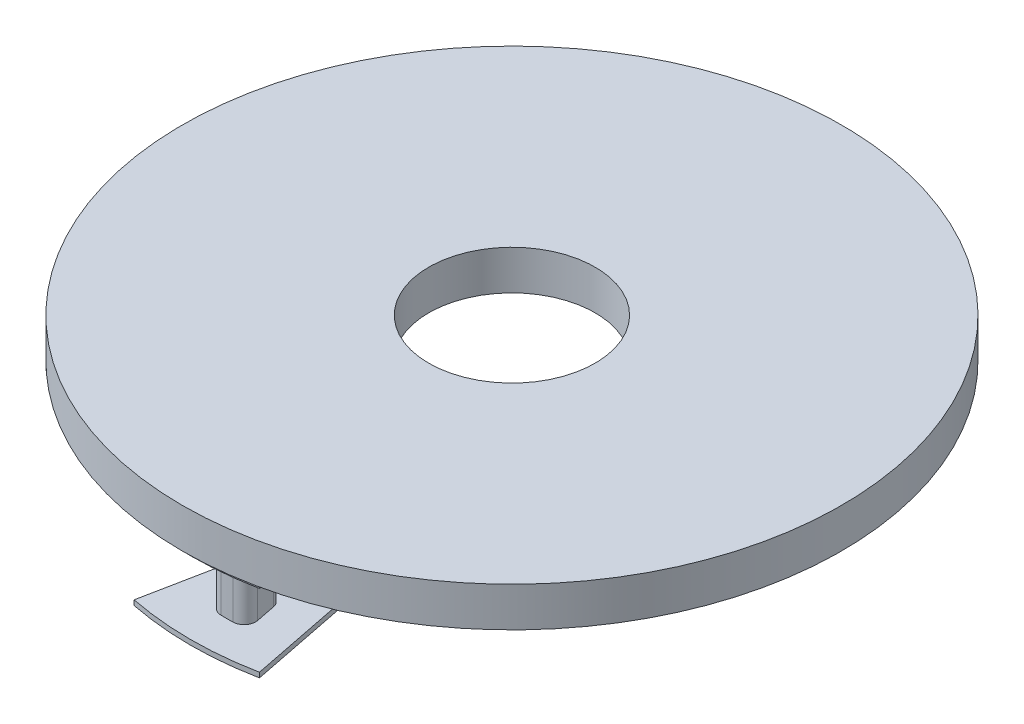
SolidWorks part; units mm, degrees
ref_plane "Front Plane" through (0, 0, 0) normal (0, 0, 1) x (1, 0, 0)
ref_plane "Top Plane" through (0, 0, 0) normal (0, 1, 0) x (1, 0, 0)
ref_plane "Right Plane" through (0, 0, 0) normal (1, 0, 0) x (0, 0, -1)
sketch "Sketch1" plane through (0, 0, 0) normal (0, 1, 0) x (1, 0, 0)
  circle A0 centre (0, 0) radius 100
  circle A1 centre (0, 0) radius 5 construction
  dimension "D1" = 200
  dimension "D2" = 10
extrude "Boss-Extrude1" add sketch "Sketch1" along normal mid plane 12
sketch "Sketch2" plane through (0, -6, 0) normal (0, -1, 0) x (1, 0, 0)
  line L0 (0, 81) -> (0, -37.3915) construction
  line L1 (11.7756, 85.47) -> (9.776, 75.4169)
  line L2 (-5.125, 86.125) -> (5.125, 86.125)
  line L3 (-5.125, 86.125) -> (-5.125, 75.875)
  line L4 (-5.125, 75.875) -> (5.125, 75.875)
  line L5 (5.125, 86.125) -> (5.125, 75.875)
  line L6 (-5.125, 86.125) -> (5.125, 75.875) construction
  line L7 (-5.125, 75.875) -> (5.125, 86.125) construction
  line L8 (11.7756, 85.47) -> (21.8287, 83.4703)
  line L9 (21.8287, 83.4703) -> (19.829, 73.4172)
  line L10 (9.776, 75.4169) -> (19.829, 73.4172)
  line L11 (28.2237, 81.5304) -> (24.3012, 72.0606)
  line L12 (28.2237, 81.5304) -> (37.6935, 77.6079)
  line L13 (37.6935, 77.6079) -> (33.771, 68.1381)
  line L14 (24.3012, 72.0606) -> (33.771, 68.1381)
  line L15 (43.5872, 74.4576) -> (37.8926, 65.9351)
  line L16 (43.5872, 74.4576) -> (52.1098, 68.763)
  line L17 (52.1098, 68.763) -> (46.4152, 60.2405)
  line L18 (37.8926, 65.9351) -> (46.4152, 60.2405)
  line L19 (57.2756, 64.5235) -> (50.0278, 57.2756)
  line L20 (57.2756, 64.5235) -> (64.5235, 57.2756)
  line L21 (64.5235, 57.2756) -> (57.2756, 50.0278)
  line L22 (50.0278, 57.2756) -> (57.2756, 50.0278)
  line L23 (68.763, 52.1098) -> (60.2405, 46.4152)
  line L24 (68.763, 52.1098) -> (74.4576, 43.5872)
  line L25 (74.4576, 43.5872) -> (65.9351, 37.8926)
  line L26 (60.2405, 46.4152) -> (65.9351, 37.8926)
  line L27 (77.6079, 37.6935) -> (68.1381, 33.771)
  line L28 (77.6079, 37.6935) -> (81.5304, 28.2237)
  line L29 (81.5304, 28.2237) -> (72.0606, 24.3012)
  line L30 (68.1381, 33.771) -> (72.0606, 24.3012)
  line L31 (83.4703, 21.8287) -> (73.4172, 19.829)
  line L32 (83.4703, 21.8287) -> (85.47, 11.7756)
  line L33 (85.47, 11.7756) -> (75.4169, 9.776)
  line L34 (73.4172, 19.829) -> (75.4169, 9.776)
  line L35 (86.125, 5.125) -> (75.875, 5.125)
  line L36 (86.125, 5.125) -> (86.125, -5.125)
  line L37 (86.125, -5.125) -> (75.875, -5.125)
  line L38 (75.875, 5.125) -> (75.875, -5.125)
  line L39 (85.47, -11.7756) -> (75.4169, -9.776)
  line L40 (85.47, -11.7756) -> (83.4703, -21.8287)
  line L41 (83.4703, -21.8287) -> (73.4172, -19.829)
  line L42 (75.4169, -9.776) -> (73.4172, -19.829)
  line L43 (81.5304, -28.2237) -> (72.0606, -24.3012)
  line L44 (81.5304, -28.2237) -> (77.6079, -37.6935)
  line L45 (77.6079, -37.6935) -> (68.1381, -33.771)
  line L46 (72.0606, -24.3012) -> (68.1381, -33.771)
  line L47 (74.4576, -43.5872) -> (65.9351, -37.8926)
  line L48 (74.4576, -43.5872) -> (68.763, -52.1098)
  line L49 (68.763, -52.1098) -> (60.2405, -46.4152)
  line L50 (65.9351, -37.8926) -> (60.2405, -46.4152)
  line L51 (64.5235, -57.2756) -> (57.2756, -50.0278)
  line L52 (64.5235, -57.2756) -> (57.2756, -64.5235)
  line L53 (57.2756, -64.5235) -> (50.0278, -57.2756)
  line L54 (57.2756, -50.0278) -> (50.0278, -57.2756)
  line L55 (52.1098, -68.763) -> (46.4152, -60.2405)
  line L56 (52.1098, -68.763) -> (43.5872, -74.4576)
  line L57 (43.5872, -74.4576) -> (37.8926, -65.9351)
  line L58 (46.4152, -60.2405) -> (37.8926, -65.9351)
  line L59 (37.6935, -77.6079) -> (33.771, -68.1381)
  line L60 (37.6935, -77.6079) -> (28.2237, -81.5304)
  line L61 (28.2237, -81.5304) -> (24.3012, -72.0606)
  line L62 (33.771, -68.1381) -> (24.3012, -72.0606)
  line L63 (21.8287, -83.4703) -> (19.829, -73.4172)
  line L64 (21.8287, -83.4703) -> (11.7756, -85.47)
  line L65 (11.7756, -85.47) -> (9.776, -75.4169)
  line L66 (19.829, -73.4172) -> (9.776, -75.4169)
  line L67 (5.125, -86.125) -> (5.125, -75.875)
  line L68 (5.125, -86.125) -> (-5.125, -86.125)
  line L69 (-5.125, -86.125) -> (-5.125, -75.875)
  line L70 (5.125, -75.875) -> (-5.125, -75.875)
  line L71 (-11.7756, -85.47) -> (-9.776, -75.4169)
  line L72 (-11.7756, -85.47) -> (-21.8287, -83.4703)
  line L73 (-21.8287, -83.4703) -> (-19.829, -73.4172)
  line L74 (-9.776, -75.4169) -> (-19.829, -73.4172)
  line L75 (-28.2237, -81.5304) -> (-24.3012, -72.0606)
  line L76 (-28.2237, -81.5304) -> (-37.6935, -77.6079)
  line L77 (-37.6935, -77.6079) -> (-33.771, -68.1381)
  line L78 (-24.3012, -72.0606) -> (-33.771, -68.1381)
  line L79 (-43.5872, -74.4576) -> (-37.8926, -65.9351)
  line L80 (-43.5872, -74.4576) -> (-52.1098, -68.763)
  line L81 (-52.1098, -68.763) -> (-46.4152, -60.2405)
  line L82 (-37.8926, -65.9351) -> (-46.4152, -60.2405)
  line L83 (-57.2756, -64.5235) -> (-50.0278, -57.2756)
  line L84 (-57.2756, -64.5235) -> (-64.5235, -57.2756)
  line L85 (-64.5235, -57.2756) -> (-57.2756, -50.0278)
  line L86 (-50.0278, -57.2756) -> (-57.2756, -50.0278)
  line L87 (-68.763, -52.1098) -> (-60.2405, -46.4152)
  line L88 (-68.763, -52.1098) -> (-74.4576, -43.5872)
  line L89 (-74.4576, -43.5872) -> (-65.9351, -37.8926)
  line L90 (-60.2405, -46.4152) -> (-65.9351, -37.8926)
  line L91 (-77.6079, -37.6935) -> (-68.1381, -33.771)
  line L92 (-77.6079, -37.6935) -> (-81.5304, -28.2237)
  line L93 (-81.5304, -28.2237) -> (-72.0606, -24.3012)
  line L94 (-68.1381, -33.771) -> (-72.0606, -24.3012)
  line L95 (-83.4703, -21.8287) -> (-73.4172, -19.829)
  line L96 (-83.4703, -21.8287) -> (-85.47, -11.7756)
  line L97 (-85.47, -11.7756) -> (-75.4169, -9.776)
  line L98 (-73.4172, -19.829) -> (-75.4169, -9.776)
  line L99 (-86.125, -5.125) -> (-75.875, -5.125)
  line L100 (-86.125, -5.125) -> (-86.125, 5.125)
  line L101 (-86.125, 5.125) -> (-75.875, 5.125)
  line L102 (-75.875, -5.125) -> (-75.875, 5.125)
  line L103 (-85.47, 11.7756) -> (-75.4169, 9.776)
  line L104 (-85.47, 11.7756) -> (-83.4703, 21.8287)
  line L105 (-83.4703, 21.8287) -> (-73.4172, 19.829)
  line L106 (-75.4169, 9.776) -> (-73.4172, 19.829)
  line L107 (-81.5304, 28.2237) -> (-72.0606, 24.3012)
  line L108 (-81.5304, 28.2237) -> (-77.6079, 37.6935)
  line L109 (-77.6079, 37.6935) -> (-68.1381, 33.771)
  line L110 (-72.0606, 24.3012) -> (-68.1381, 33.771)
  line L111 (-74.4576, 43.5872) -> (-65.9351, 37.8926)
  line L112 (-74.4576, 43.5872) -> (-68.763, 52.1098)
  line L113 (-68.763, 52.1098) -> (-60.2405, 46.4152)
  line L114 (-65.9351, 37.8926) -> (-60.2405, 46.4152)
  line L115 (-64.5235, 57.2756) -> (-57.2756, 50.0278)
  line L116 (-64.5235, 57.2756) -> (-57.2756, 64.5235)
  line L117 (-57.2756, 64.5235) -> (-50.0278, 57.2756)
  line L118 (-57.2756, 50.0278) -> (-50.0278, 57.2756)
  line L119 (-52.1098, 68.763) -> (-46.4152, 60.2405)
  line L120 (-52.1098, 68.763) -> (-43.5872, 74.4576)
  line L121 (-43.5872, 74.4576) -> (-37.8926, 65.9351)
  line L122 (-46.4152, 60.2405) -> (-37.8926, 65.9351)
  line L123 (-37.6935, 77.6079) -> (-33.771, 68.1381)
  line L124 (-37.6935, 77.6079) -> (-28.2237, 81.5304)
  line L125 (-28.2237, 81.5304) -> (-24.3012, 72.0606)
  line L126 (-33.771, 68.1381) -> (-24.3012, 72.0606)
  line L127 (-21.8287, 83.4703) -> (-19.829, 73.4172)
  line L128 (-21.8287, 83.4703) -> (-11.7756, 85.47)
  line L129 (-11.7756, 85.47) -> (-9.776, 75.4169)
  line L130 (-19.829, 73.4172) -> (-9.776, 75.4169)
  point P3 (0, 81)
  point P87 (0, 0)
  dimension "D1" = 10.25
  dimension "D2" = 10.25
  dimension "D3" = 81
  dimension "D4" = 32
extrude "Cut-Extrude1" cut sketch "Sketch2" against normal blind 10
sketch "Sketch3" plane through (0, 6, 0) normal (0, 1, 0) x (1, 0, 0)
  circle A0 centre (0, 0) radius 25.25
  dimension "D1" = 50.5
extrude "Cut-Extrude2" cut sketch "Sketch3" against normal through all both and the other way through all
sketch "Sketch4" plane through (0, 6, 0) normal (0, 1, 0) x (1, 0, 0)
  line L0 (0, 0) -> (0, 64.4809) construction
  line L1 (-5, 37.1652) -> (-5, 47.1652)
  line L2 (-5, 47.1652) -> (5, 47.1652)
  line L3 (5, 47.1652) -> (5, 37.1652)
  line L4 (47.1652, -5) -> (37.1652, -5)
  line L5 (47.1652, 5) -> (47.1652, -5)
  line L6 (37.1652, 5) -> (47.1652, 5)
  line L7 (-5, -47.1652) -> (-5, -37.1652)
  line L8 (5, -47.1652) -> (-5, -47.1652)
  line L9 (5, -37.1652) -> (5, -47.1652)
  line L10 (-47.1652, 5) -> (-37.1652, 5)
  line L11 (-47.1652, -5) -> (-47.1652, 5)
  line L12 (-37.1652, -5) -> (-47.1652, -5)
  arc A0 (-5, 37.1652) -> (-37.1652, 5) centre (0, 0) ccw
  arc A1 (0, 37.5) -> (-5, 37.1652) centre (0, 0) ccw construction
  arc A2 (5, 37.1652) -> (0, 37.5) centre (0, 0) ccw construction
  arc A3 (37.1652, -5) -> (37.1652, 5) centre (0, 0) ccw construction
  arc A4 (37.1652, 5) -> (5, 37.1652) centre (0, 0) ccw
  arc A5 (-37.1652, 5) -> (-37.1652, -5) centre (0, 0) ccw construction
  arc A6 (-37.1652, -5) -> (-5, -37.1652) centre (0, 0) ccw
  arc A7 (-5, -37.1652) -> (5, -37.1652) centre (0, 0) ccw construction
  arc A8 (5, -37.1652) -> (37.1652, -5) centre (0, 0) ccw
  point P6 (0, 47.1652)
  point P24 (0, 0)
  dimension "D1" = 75
  dimension "D2" = 10
  dimension "D3" = 10
  dimension "D4" = 4
extrude "Cut-Extrude-Thin1" [suppressed] cut sketch "Sketch4" against normal through all both and the other way through all thin
sketch "Sketch5" plane through (0, -6, 0) normal (0, -1, 0) x (1, 0, 0)
  line L0 (0, 0) -> (0, 106.3034) construction
  line L1 (-19.0213, 95.6266) -> (-12.1931, 61.2991)
  line L2 (-11.7756, 85.47) -> (-21.8287, 83.4703) construction
  line L3 (19.0213, 95.6266) -> (12.1931, 61.2991)
  line L4 (3.6837, 82.592) -> (2.4934, 76.608)
  line L5 (-3.6837, 82.592) -> (-2.4934, 76.608)
  line L6 (-4.1426, 84.899) -> (-2.1673, 74.9687) construction
  line L7 (4.1426, 84.899) -> (2.1673, 74.9687) construction
  line L8 (-12.1931, 61.2991) -> (12.1931, 61.2991)
  arc A0 (-19.0213, 95.6266) -> (19.0213, 95.6266) centre (0, 0) cw
  circle A1 centre (0, 0) radius 100 construction
  arc A2 (-12.1931, 61.2991) -> (0, 62.5) centre (0, 0) cw construction
  arc A3 (-0.518, 74.9982) -> (0.518, 74.9982) centre (0, 0) cw
  arc A4 (-1.7636, 84.9817) -> (1.7636, 84.9817) centre (0, 0) cw
  arc A5 (-2.1673, 74.9687) -> (2.1673, 74.9687) centre (0, 0) cw construction
  arc A6 (-2.4934, 76.608) -> (-0.518, 74.9982) centre (-0.5318, 76.9982) ccw
  arc A7 (2.4934, 76.608) -> (0.518, 74.9982) centre (0.5318, 76.9982) cw
  arc A8 (-4.1426, 84.899) -> (4.1426, 84.899) centre (0, 0) cw construction
  arc A9 (3.6837, 82.592) -> (1.7636, 84.9817) centre (1.7221, 82.9821) ccw
  arc A10 (-3.6837, 82.592) -> (-1.7636, 84.9817) centre (-1.7221, 82.9821) cw
  arc A11 (0, 62.5) -> (12.1931, 61.2991) centre (0, 0) cw construction
  arc A12 (-12.1931, 61.2991) -> (12.1931, 61.2991) centre (0, 0) cw construction
  point P13 (-16.8022, 84.4701)
  dimension "D3" = 62.5
  dimension "D5" = 2
  dimension "D1" = 35
  dimension "D2" = 11.25
  dimension "D4" = 12.5
extrude "Boss-Extrude2" add sketch "Sketch5" along normal blind 1.5 from offset 1
sketch "Sketch6" plane through (0, -8.5, 0) normal (0, -1, 0) x (1, 0, 0)
  line L0 (-3.6837, 82.592) -> (-2.4934, 76.608) construction
  line L1 (2.4934, 76.608) -> (3.6837, 82.592) construction
  line L2 (-3.6837, 82.592) -> (-2.4934, 76.608)
  line L3 (2.4934, 76.608) -> (3.6837, 82.592)
  line L4 (-5.1548, 82.2993) -> (-3.9646, 76.3153)
  line L5 (3.9646, 76.3153) -> (5.1548, 82.2993)
  arc A0 (0.518, 74.9982) -> (-0.518, 74.9982) centre (0, 0) ccw construction
  arc A1 (0.518, 74.9982) -> (2.4934, 76.608) centre (0.5318, 76.9982) ccw construction
  arc A2 (-2.4934, 76.608) -> (-0.518, 74.9982) centre (-0.5318, 76.9982) ccw construction
  arc A3 (-1.7636, 84.9817) -> (-3.6837, 82.592) centre (-1.7221, 82.9821) ccw construction
  arc A4 (1.7636, 84.9817) -> (-1.7636, 84.9817) centre (0, 0) ccw construction
  arc A5 (3.6837, 82.592) -> (1.7636, 84.9817) centre (1.7221, 82.9821) ccw construction
  arc A6 (0.518, 74.9982) -> (-0.518, 74.9982) centre (0, 0) ccw
  arc A7 (0.518, 74.9982) -> (2.4934, 76.608) centre (0.5318, 76.9982) ccw
  arc A8 (-2.4934, 76.608) -> (-0.518, 74.9982) centre (-0.5318, 76.9982) ccw
  arc A9 (-1.7636, 84.9817) -> (-3.6837, 82.592) centre (-1.7221, 82.9821) ccw
  arc A10 (1.7636, 84.9817) -> (-1.7636, 84.9817) centre (0, 0) ccw
  arc A11 (3.6837, 82.592) -> (1.7636, 84.9817) centre (1.7221, 82.9821) ccw
  arc A12 (-1.7947, 86.4814) -> (-5.1548, 82.2993) centre (-1.7221, 82.9821) ccw
  arc A13 (-3.9646, 76.3153) -> (-0.5076, 73.4982) centre (-0.5318, 76.9982) ccw
  arc A14 (0.5076, 73.4982) -> (-0.5076, 73.4982) centre (0, 0) ccw
  arc A15 (0.5076, 73.4982) -> (3.9646, 76.3153) centre (0.5318, 76.9982) ccw
  arc A16 (5.1548, 82.2993) -> (1.7947, 86.4814) centre (1.7221, 82.9821) ccw
  arc A17 (1.7947, 86.4814) -> (-1.7947, 86.4814) centre (0, 0) ccw
  dimension "D1" = 1.5
extrude "Boss-Extrude3" add sketch "Sketch6" along normal blind 22
sketch "Sketch7" plane through (0, -30.5, 0) normal (0, -1, 0) x (1, 0, 0)
  line L1 (-3.6837, 82.592) -> (-2.4934, 76.608) construction
  line L2 (-19.0213, 95.6266) -> (-12.1931, 61.2991)
  line L3 (12.1931, 61.2991) -> (19.0213, 95.6266)
  line L4 (-19.0213, 95.6266) -> (-12.1931, 61.2991)
  line L5 (12.1931, 61.2991) -> (19.0213, 95.6266)
  line L6 (-3.6837, 82.592) -> (-2.4934, 76.608)
  line L7 (2.4934, 76.608) -> (3.6837, 82.592) construction
  line L8 (2.4934, 76.608) -> (3.6837, 82.592)
  line L13 (-12.1931, 61.2991) -> (12.1931, 61.2991)
  line L14 (-12.1931, 61.2991) -> (12.1931, 61.2991)
  arc A2 (19.0213, 95.6266) -> (-19.0213, 95.6266) centre (0, 0) ccw
  arc A4 (19.0213, 95.6266) -> (-19.0213, 95.6266) centre (0, 0) ccw
  arc A8 (-1.7636, 84.9817) -> (-3.6837, 82.592) centre (-1.7221, 82.9821) ccw construction
  arc A9 (1.7636, 84.9817) -> (-1.7636, 84.9817) centre (0, 0) ccw construction
  arc A10 (-1.7636, 84.9817) -> (-3.6837, 82.592) centre (-1.7221, 82.9821) ccw
  arc A11 (0.518, 74.9982) -> (2.4934, 76.608) centre (0.5318, 76.9982) ccw construction
  arc A12 (3.6837, 82.592) -> (1.7636, 84.9817) centre (1.7221, 82.9821) ccw construction
  arc A13 (0.518, 74.9982) -> (2.4934, 76.608) centre (0.5318, 76.9982) ccw
  arc A14 (3.6837, 82.592) -> (1.7636, 84.9817) centre (1.7221, 82.9821) ccw
  arc A15 (1.7636, 84.9817) -> (-1.7636, 84.9817) centre (0, 0) ccw
  arc A16 (0.518, 74.9982) -> (-0.518, 74.9982) centre (0, 0) ccw construction
  arc A17 (-2.4934, 76.608) -> (-0.518, 74.9982) centre (-0.5318, 76.9982) ccw construction
  arc A18 (-2.4934, 76.608) -> (-0.518, 74.9982) centre (-0.5318, 76.9982) ccw
  arc A19 (0.518, 74.9982) -> (-0.518, 74.9982) centre (0, 0) ccw
  dimension "D1" = 0
extrude "Boss-Extrude4" add sketch "Sketch7" along normal blind 1.5
sketch "Sketch8" plane through (0, -7, 0) normal (0, 1, 0) x (1, 0, 0)
  line L0 (-12.3921, -62.2991) -> (12.3921, -62.2991)
  line L1 (-19.0213, -95.6266) -> (-12.1931, -61.2991) construction
  line L2 (12.1931, -61.2991) -> (19.0213, -95.6266) construction
  line L3 (-12.1931, -61.2991) -> (12.1931, -61.2991) construction
  line L4 (-12.3921, -62.2991) -> (-12.1931, -61.2991)
  line L5 (-12.1931, -61.2991) -> (12.1931, -61.2991)
  line L6 (12.1931, -61.2991) -> (12.3921, -62.2991)
  dimension "D1" = 1
extrude "Cut-Extrude3" cut sketch "Sketch8" against normal through all both and the other way through all
sketch "Sketch9" plane through (0, -7, 0) normal (0, 1, 0) x (1, 0, 0)
  line L0 (-2.9838, -76.5104) -> (-4.1741, -82.4944)
  line L1 (4.1741, -82.4944) -> (2.9838, -76.5104)
  line L2 (-2.4934, -76.608) -> (-3.6837, -82.592)
  line L3 (3.6837, -82.592) -> (2.4934, -76.608)
  line L4 (-2.4934, -76.608) -> (-3.6837, -82.592) construction
  line L5 (3.6837, -82.592) -> (2.4934, -76.608) construction
  arc A0 (-4.1741, -82.4944) -> (-1.774, -85.4816) centre (-1.7221, -82.9821) ccw
  arc A1 (-1.774, -85.4816) -> (1.774, -85.4816) centre (0, 0) ccw
  arc A2 (1.774, -85.4816) -> (4.1741, -82.4944) centre (1.7221, -82.9821) ccw
  arc A3 (2.9838, -76.5104) -> (0.5145, -74.4982) centre (0.5318, -76.9982) ccw
  arc A4 (-0.5145, -74.4982) -> (0.5145, -74.4982) centre (0, 0) ccw
  arc A5 (-0.5145, -74.4982) -> (-2.9838, -76.5104) centre (-0.5318, -76.9982) ccw
  arc A6 (-0.518, -74.9982) -> (-2.4934, -76.608) centre (-0.5318, -76.9982) ccw
  arc A7 (-0.518, -74.9982) -> (0.518, -74.9982) centre (0, 0) ccw
  arc A8 (2.4934, -76.608) -> (0.518, -74.9982) centre (0.5318, -76.9982) ccw
  arc A9 (1.7636, -84.9817) -> (3.6837, -82.592) centre (1.7221, -82.9821) ccw
  arc A10 (-1.7636, -84.9817) -> (1.7636, -84.9817) centre (0, 0) ccw
  arc A11 (-3.6837, -82.592) -> (-1.7636, -84.9817) centre (-1.7221, -82.9821) ccw
  arc A12 (-0.518, -74.9982) -> (-2.4934, -76.608) centre (-0.5318, -76.9982) ccw construction
  arc A13 (-0.518, -74.9982) -> (0.518, -74.9982) centre (0, 0) ccw construction
  arc A14 (2.4934, -76.608) -> (0.518, -74.9982) centre (0.5318, -76.9982) ccw construction
  arc A15 (1.7636, -84.9817) -> (3.6837, -82.592) centre (1.7221, -82.9821) ccw construction
  arc A16 (-1.7636, -84.9817) -> (1.7636, -84.9817) centre (0, 0) ccw construction
  arc A17 (-3.6837, -82.592) -> (-1.7636, -84.9817) centre (-1.7221, -82.9821) ccw construction
  dimension "D1" = 0
  dimension "D2" = 0.5
extrude "Cut-Extrude4" cut sketch "Sketch9" against normal through all both and the other way through all
